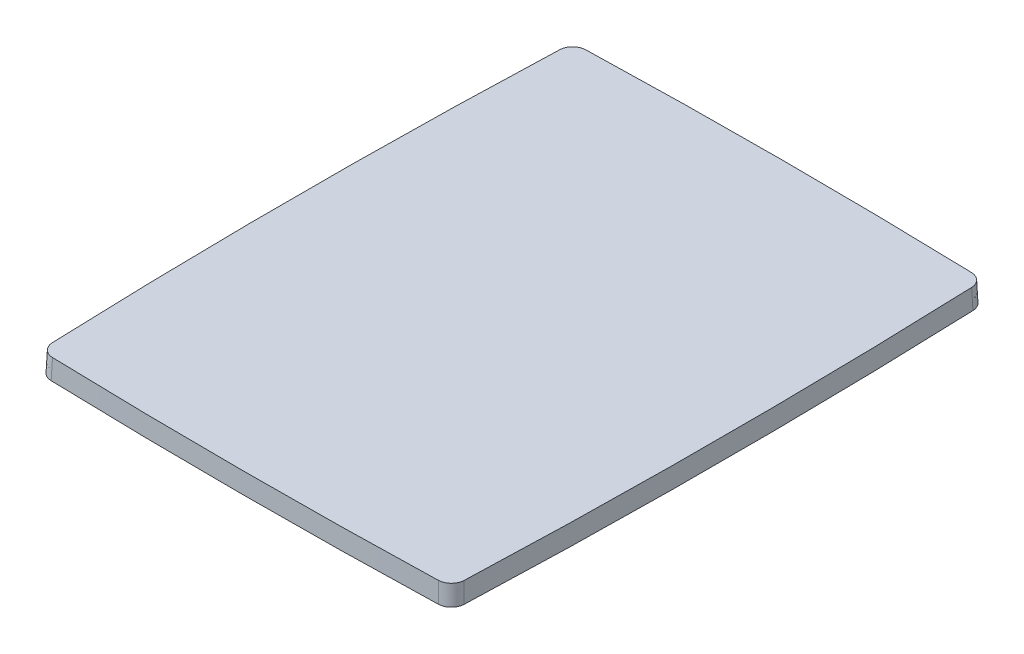
SolidWorks part; units mm, degrees
ref_plane "Front Plane" through (0, 0, 0) normal (0, 0, 1) x (1, 0, 0)
ref_plane "Top Plane" through (0, 0, 0) normal (0, 1, 0) x (1, 0, 0)
ref_plane "Right Plane" through (0, 0, 0) normal (1, 0, 0) x (0, 0, -1)
sketch "Sketch1" plane through (0, 0, 0) normal (0, 1, 0) x (1, 0, 0)
  line L0 (0, 0) -> (0, -500) construction
  line L1 (-13.8, 18.18) -> (13.8, 18.18) construction
  line L2 (-13.8, 18.18) -> (-13.8, -18.18) construction
  line L3 (-13.8, -18.18) -> (13.8, -18.18) construction
  line L4 (13.8, 18.18) -> (13.8, -18.18) construction
  line L5 (-13.8, 18.18) -> (13.8, -18.18) construction
  line L6 (-13.8, -18.18) -> (13.8, 18.18) construction
  line L7 (-14.8, 19.18) -> (14.8, 19.18) construction
  line L8 (-14.8, 19.18) -> (-14.8, -19.18) construction
  line L9 (-14.8, -19.18) -> (14.8, -19.18) construction
  line L10 (14.8, 19.18) -> (14.8, -19.18) construction
  line L11 (-14.8, 19.18) -> (14.8, -19.18) construction
  line L12 (-14.8, -19.18) -> (14.8, 19.18) construction
  line L13 (-19.8, 24.18) -> (19.8, 24.18) construction
  line L14 (-19.8, 24.18) -> (-19.8, -24.18) construction
  line L15 (-19.8, -24.18) -> (19.8, -24.18) construction
  line L16 (19.8, 24.18) -> (19.8, -24.18) construction
  line L17 (-19.8, 24.18) -> (19.8, -24.18) construction
  line L18 (-19.8, -24.18) -> (19.8, 24.18) construction
  line L19 (0, 0) -> (500, 0) construction
  line L20 (0, 0) -> (0, 53.4587) construction
  line L21 (0, 0) -> (-83.3147, 0) construction
  arc A4 (-15.399, 19.9409) -> (-15.399, -19.9409) centre (480.2, 0) ccw
  arc A7 (15.399, 19.9409) -> (-15.399, 19.9409) centre (0, -475.82) ccw
  arc A8 (15.399, 19.9409) -> (15.399, -19.9409) centre (-480.2, 0) cw
  arc A11 (15.399, -19.9409) -> (-15.399, -19.9409) centre (0, 475.82) cw
  point P0 (0, 0)
  point P6 (0, 0)
  point P11 (0, 0)
  dimension "D7" = 496
  dimension "D10" = 500
  dimension "D13" = 992
  dimension "D1" = 27.6
  dimension "D2" = 36.36
  dimension "D3" = 1
  dimension "D4" = 1
  dimension "D5" = 5
  dimension "D6" = 5
  dimension "D8" = 500
  dimension "D9" = 500
  dimension "D11" = 500
extrude "Boss-Extrude1" add sketch "Sketch1" along normal blind 1.5 draft 2
fillet "Fillet1" radius 1 4 edges
